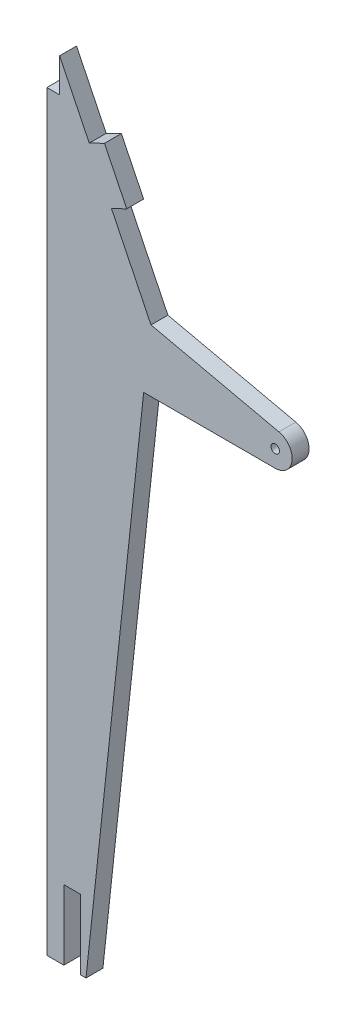
SolidWorks part; units mm, degrees
ref_plane "前视基准面" through (0, 0, 0) normal (0, 0, 1) x (1, 0, 0)
ref_plane "上视基准面" through (0, 0, 0) normal (0, 1, 0) x (1, 0, 0)
ref_plane "右视基准面" through (0, 0, 0) normal (1, 0, 0) x (0, 0, -1)
sketch "草图1" plane through (0, 0, 0) normal (0, 0, 1) x (1, 0, 0)
  line L0 (11.5654, 98.1806) -> (11.5654, 94.1806)
  line L1 (11.5654, 94.1806) -> (10.0654, 94.1806)
  line L2 (10.0654, 94.1806) -> (10.0654, 5.2978)
  line L3 (11.5654, 98.1806) -> (15.0724, 90.9902)
  line L4 (15.0724, 90.9902) -> (16.8699, 91.867)
  line L5 (16.8699, 91.867) -> (19.5002, 86.4742)
  line L6 (19.5002, 86.4742) -> (17.7026, 85.5974)
  line L7 (17.7026, 85.5974) -> (21.074, 78.685)
  line L8 (10.0654, 5.2978) -> (12.0654, 5.2978)
  line L9 (12.0654, 5.2978) -> (12.0654, 13.5478)
  line L10 (12.0654, 13.5478) -> (14.0654, 13.5478)
  line L11 (21.5062, 68.6806) -> (14.6864, 5.2978)
  line L12 (14.0654, 13.5478) -> (14.0654, 5.2978)
  line L13 (14.0654, 5.2978) -> (14.6864, 5.2978)
  line L14 (22.373, 76.0216) -> (37.5026, 72.6322)
  line L15 (37.0654, 68.6806) -> (21.5062, 68.6806)
  line L16 (21.074, 78.685) -> (22.373, 76.0216)
  circle A0 centre (37.0654, 70.6806) radius 0.5
  arc A1 (37.0654, 68.6806) -> (37.0654, 72.6806) centre (37.0654, 70.6806) ccw
extrude "凸台-拉伸1" add sketch "草图1" along normal blind 2
